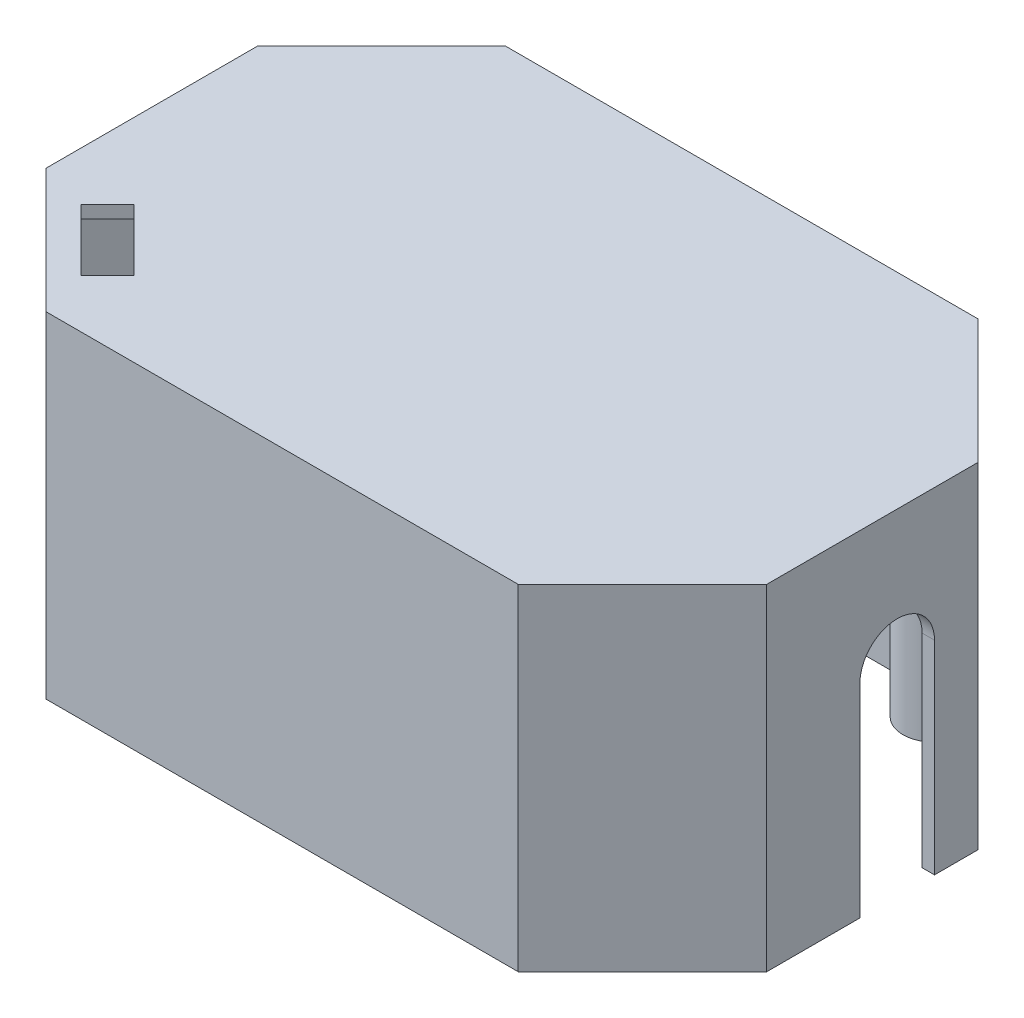
SolidWorks part; units mm, degrees
ref_plane "Front" through (0, 0, 0) normal (0, 0, 1) x (1, 0, 0)
ref_plane "Top" through (0, 0, 0) normal (0, 1, 0) x (1, 0, 0)
ref_plane "Right" through (0, 0, 0) normal (1, 0, 0) x (0, 0, -1)
sketch "Sketch1" plane through (0, 0, 0) normal (0, 1, 0) x (1, 0, 0)
  line L0 (38, -32.4216) -> (-38, -32.4216)
  line L1 (-58, -12.4216) -> (-38, -32.4216)
  line L2 (-58, -12.4216) -> (-58, 21.5784)
  line L3 (-38, 41.5784) -> (-58, 21.5784)
  line L4 (-38, 41.5784) -> (38, 41.5784)
  line L6 (58, 21.5784) -> (38, 41.5784)
  line L7 (58, 21.5784) -> (58, -12.4216)
  line L8 (38, -32.4216) -> (58, -12.4216)
  line L13 (-37.1716, 39.5784) -> (-56, 20.7499)
  line L14 (-56, -11.5932) -> (-56, 20.7499)
  line L15 (-56, -11.5932) -> (-37.1716, -30.4216)
  line L16 (37.1716, -30.4216) -> (-37.1716, -30.4216)
  line L17 (37.1716, -30.4216) -> (56, -11.5932)
  line L18 (56, 20.75) -> (56, -11.5932)
  line L19 (56, 20.75) -> (37.1716, 39.5784)
  line L20 (-37.1716, 39.5784) -> (37.1716, 39.5784)
  point P5 (0, -32.4216)
  dimension "D1" = 76
  dimension "D2" = 20
  dimension "D3" = 20
  dimension "D4" = 34
  dimension "D5" = 20
  dimension "D6" = 20
  dimension "D7" = 2
extrude "Boss-Extrude1" add sketch "Sketch1" along normal blind 52
sketch "Sketch2" plane through (0, 52, 0) normal (0, 1, 0) x (1, 0, 0)
  line L8 (38, -32.4216) -> (58, -12.4216)
  line L9 (58, -12.4216) -> (58, 21.5784)
  line L10 (58, 21.5784) -> (38, 41.5784)
  line L11 (38, 41.5784) -> (-38, 41.5784)
  line L12 (-38, 41.5784) -> (-58, 21.5784)
  line L13 (-58, 21.5784) -> (-58, -12.4216)
  line L14 (-58, -12.4216) -> (-38, -32.4216)
  line L15 (-38, -32.4216) -> (38, -32.4216)
  line L16 (38, -32.4216) -> (58, -12.4216)
  line L17 (58, -12.4216) -> (58, 21.5784)
  line L18 (58, 21.5784) -> (38, 41.5784)
  line L19 (38, 41.5784) -> (-38, 41.5784)
  line L20 (-38, 41.5784) -> (-58, 21.5784)
  line L21 (-58, 21.5784) -> (-58, -12.4216)
  line L22 (-58, -12.4216) -> (-38, -32.4216)
  line L23 (-38, -32.4216) -> (38, -32.4216)
  dimension "D1" = 0
extrude "Boss-Extrude2" add sketch "Sketch2" along normal blind 2
sketch "Sketch3" plane through (0, 52, 0) normal (0, -1, 0) x (1, 0, 0)
  line L0 (38, -41.5784) -> (-38, -41.5784) construction
  line L1 (58, -21.5784) -> (38, -41.5784) construction
  line L2 (-38, -41.5784) -> (-58, -21.5784) construction
  line L3 (-58, 12.4216) -> (-38, 32.4216) construction
  line L4 (-38, 32.4216) -> (38, 32.4216) construction
  line L5 (38, 32.4216) -> (58, 12.4216) construction
  circle A0 centre (35.9289, -36.5784) radius 5
  circle A1 centre (-35.9289, -36.5784) radius 5
  circle A2 centre (-35.9289, 27.4216) radius 5
  circle A3 centre (35.9289, 27.4216) radius 5
  dimension "D1" = 10
extrude "Boss-Extrude3" add sketch "Sketch3" along normal up to surface (52 mm away) up to face at (0, 0, -4.5784)
sketch "Sketch4" plane through (0, 0, 0) normal (0, -1, 0) x (-1, 0, 0)
  circle A0 centre (-35.9289, 36.5784) radius 2.5
  circle A1 centre (35.9289, 36.5784) radius 2.5
  circle A2 centre (35.9289, -27.4216) radius 2.5
  circle A4 centre (-35.9289, -27.4216) radius 2.5
  dimension "D1" = 5
extrude "Cut-Extrude1" cut sketch "Sketch4" against normal blind 15
sketch "Sketch5" plane through (0, 54, 0) normal (0, 1, 0) x (1, 0, 0)
  line L0 (-50.1213, -14.6435) -> (-40.2218, -24.5429)
  line L1 (-40.2218, -24.5429) -> (-35.9792, -20.3003)
  line L2 (-35.9792, -20.3003) -> (-45.8787, -10.4008)
  line L3 (-45.8787, -10.4008) -> (-50.1213, -14.6435)
  line L5 (-58, -12.4216) -> (-38, -32.4216) construction
  line L6 (-48, -22.4216) -> (-27.9334, -2.355) construction
  point P9 (-45.1716, -19.5932)
  dimension "D1" = 6
  dimension "D2" = 14
  dimension "D3" = 4
extrude "Cut-Extrude2" cut sketch "Sketch5" against normal blind 15
sketch "Sketch6" plane through (-58, 0, 0) normal (-1, 0, 0) x (0, 0, 1)
  line L0 (-14.5784, 0) -> (-14.5784, 32.7131)
  line L1 (-21.5784, 0) -> (12.4216, 0) construction
  line L2 (-2.5784, 32.7131) -> (-2.5784, 0)
  line L3 (-14.5784, 0) -> (-2.5784, 0)
  line L4 (-21.5784, 54) -> (-21.5784, 0) construction
  arc A0 (-14.5784, 32.7131) -> (-2.5784, 32.7131) centre (-8.5784, 32.7131) cw
  dimension "D1" = 12
  dimension "D2" = 7
extrude "Cut-Extrude3" cut sketch "Sketch6" against normal up to surface (116 mm away) up to face at (58, 27, -4.5784)
